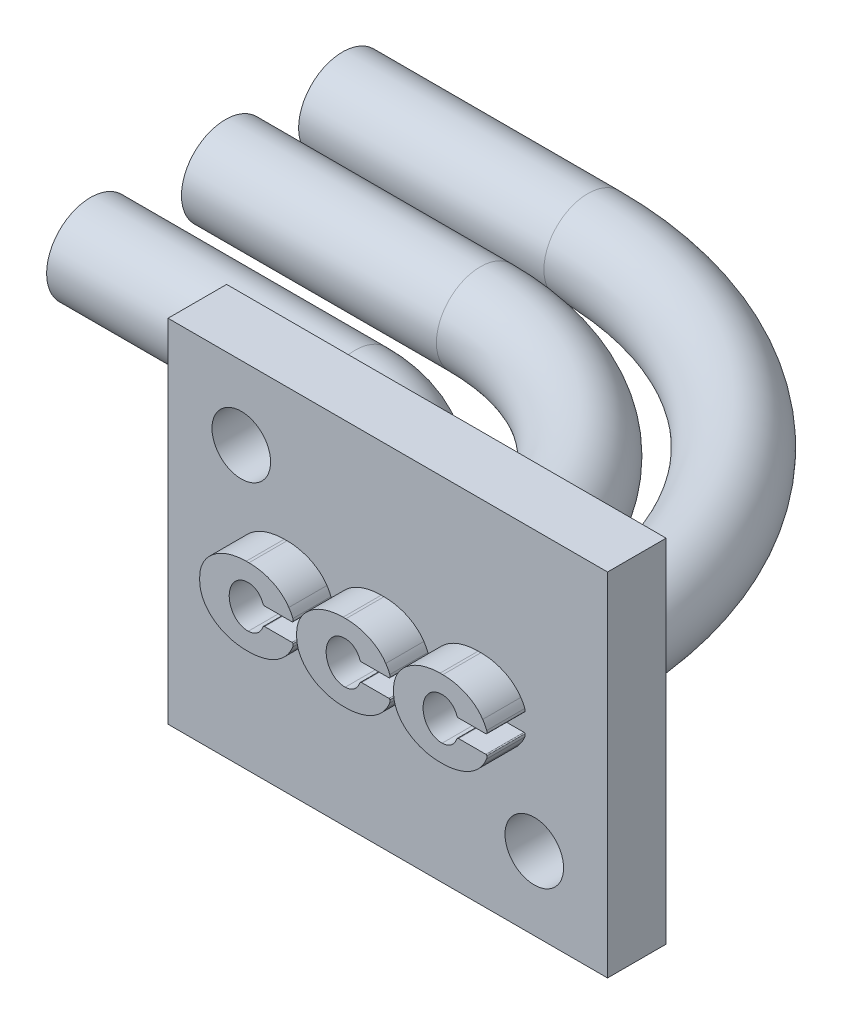
SolidWorks part; units mm, degrees
ref_plane "Front Plane" through (0, 0, 0) normal (0, 0, 1) x (1, 0, 0)
ref_plane "Top Plane" through (0, 0, 0) normal (0, 1, 0) x (1, 0, 0)
ref_plane "Right Plane" through (0, 0, 0) normal (1, 0, 0) x (0, 0, -1)
sketch "Sketch1" plane through (0, 0, 0) normal (0, 0, 1) x (1, 0, 0)
  line L1 (-7.5, 6) -> (7.5, 6)
  line L2 (-7.5, 6) -> (-7.5, -6)
  line L3 (-7.5, -6) -> (7.5, -6)
  line L4 (7.5, 6) -> (7.5, -6)
  line L5 (-7.5, 6) -> (7.5, -6) construction
  line L6 (-7.5, -6) -> (7.5, 6) construction
  point P0 (0, 0)
  dimension "D1" = 15
  dimension "D2" = 12
extrude "Boss-Extrude1" add sketch "Sketch1" along normal blind 2
sketch "Sketch2" plane through (0, 0, 2) normal (0, 0, 1) x (1, 0, 0)
  line L0 (0.4072, 0.4423) -> (1.3431, 0.4423)
  line L1 (-0.1301, 1.4531) -> (-0.2238, 1.4531)
  line L2 (-1.8094, 0.2019) -> (-1.8094, 0.0718)
  line L3 (-0.2238, -1.1794) -> (-0.1301, -1.1794)
  line L4 (1.3385, -0.1647) -> (0.4072, -0.1647)
  line L5 (-2.9011, 0.4423) -> (-1.9652, 0.4423)
  line L6 (-3.4384, 1.4531) -> (-3.5321, 1.4531)
  line L7 (-5.1177, 0.2019) -> (-5.1177, 0.0718)
  line L8 (-3.5321, -1.1794) -> (-3.4384, -1.1794)
  line L9 (-1.9698, -0.1647) -> (-2.9011, -0.1647)
  line L10 (3.7155, 0.4423) -> (4.6514, 0.4423)
  line L11 (3.1782, 1.4531) -> (3.0846, 1.4531)
  line L12 (1.4989, 0.2019) -> (1.4989, 0.0718)
  line L13 (3.0846, -1.1794) -> (3.1782, -1.1794)
  line L14 (4.6469, -0.1647) -> (3.7155, -0.1647)
  arc A0 (0.3456, 0.4859) -> (0.4072, 0.4423) centre (0.4072, 0.5078) ccw
  arc A1 (1.3431, 0.4423) -> (1.3723, 0.4672) centre (1.3386, 0.4772) ccw
  arc A2 (1.3723, 0.4672) -> (1.3681, 0.5547) centre (1.1917, 0.5024) ccw
  arc A3 (1.3681, 0.5547) -> (1.231, 0.812) centre (0.2861, 0.1431) ccw
  arc A4 (1.231, -0.5382) -> (1.3634, -0.2919) centre (0.2955, 0.1234) ccw
  arc A5 (1.3634, -0.2919) -> (1.3732, -0.1939) centre (1.1919, -0.2252) ccw
  arc A6 (1.3732, -0.1939) -> (1.3385, -0.1647) centre (1.3385, -0.1999) ccw
  arc A7 (0.4072, -0.1647) -> (0.3456, -0.2083) centre (0.4072, -0.2302) ccw
  arc A8 (-2.9627, 0.4859) -> (-2.9011, 0.4423) centre (-2.9011, 0.5078) ccw
  arc A9 (-1.9652, 0.4423) -> (-1.936, 0.4672) centre (-1.9697, 0.4772) ccw
  arc A10 (-1.936, 0.4672) -> (-1.9402, 0.5547) centre (-2.1166, 0.5024) ccw
  arc A11 (-1.9402, 0.5547) -> (-2.0773, 0.812) centre (-3.0222, 0.1431) ccw
  arc A12 (-2.0773, -0.5382) -> (-1.9449, -0.2919) centre (-3.0128, 0.1234) ccw
  arc A13 (-1.9449, -0.2919) -> (-1.9351, -0.1939) centre (-2.1164, -0.2252) ccw
  arc A14 (-1.9351, -0.1939) -> (-1.9698, -0.1647) centre (-1.9698, -0.1999) ccw
  arc A15 (-2.9011, -0.1647) -> (-2.9627, -0.2083) centre (-2.9011, -0.2302) ccw
  arc A16 (3.6539, 0.4859) -> (3.7155, 0.4423) centre (3.7155, 0.5078) ccw
  arc A17 (4.6514, 0.4423) -> (4.6806, 0.4672) centre (4.6469, 0.4772) ccw
  arc A18 (4.6806, 0.4672) -> (4.6764, 0.5547) centre (4.5, 0.5024) ccw
  arc A19 (4.6764, 0.5547) -> (4.5393, 0.812) centre (3.5944, 0.1431) ccw
  arc A20 (4.5393, -0.5382) -> (4.6717, -0.2919) centre (3.6038, 0.1234) ccw
  arc A21 (4.6717, -0.2919) -> (4.6815, -0.1939) centre (4.5002, -0.2252) ccw
  arc A22 (4.6815, -0.1939) -> (4.6469, -0.1647) centre (4.6469, -0.1999) ccw
  arc A23 (3.7155, -0.1647) -> (3.6539, -0.2083) centre (3.7155, -0.2302) ccw
  ellipse E0 centre (-0.1827, 0.137) end of major axis (-0.1791, -0.5801) minor radius 0.6209 (-0.2107, 0.8534) -> (-0.1509, -0.5792) ccw
  ellipse E1 centre (-0.2388, 0.137) end of major axis (0.0439, 0.8186) minor radius 0.6039 (0.3456, 0.4859) -> (-0.2107, 0.8534) ccw
  ellipse E2 centre (-0.2522, 0.1514) end of major axis (1.3906, 0.3966) minor radius 1.2925 (1.231, 0.812) -> (-0.1301, 1.4531) ccw
  ellipse E3 centre (-0.1614, 0.1527) end of major axis (-1.8063, 0.2821) minor radius 1.2979 (-0.2238, 1.4531) -> (-1.8094, 0.2019) ccw
  ellipse E4 centre (-0.1614, 0.121) end of major axis (1.4835, 0.2504) minor radius 1.2979 (-1.8094, 0.0718) -> (-0.2238, -1.1794) ccw
  ellipse E5 centre (-0.2522, 0.1223) end of major axis (-1.895, 0.3674) minor radius 1.2925 (-0.1301, -1.1794) -> (1.231, -0.5382) ccw
  ellipse E6 centre (-0.2388, 0.1406) end of major axis (0.0439, -0.541) minor radius 0.6039 (-0.1509, -0.5792) -> (0.3456, -0.2083) ccw
  ellipse E7 centre (-3.5471, 0.137) end of major axis (-3.2644, 0.8186) minor radius 0.6039 (-2.9627, 0.4859) -> (-3.519, 0.8534) ccw
  ellipse E8 centre (-3.5605, 0.1514) end of major axis (-1.9177, 0.3966) minor radius 1.2925 (-2.0773, 0.812) -> (-3.4384, 1.4531) ccw
  ellipse E9 centre (-3.4697, 0.1527) end of major axis (-5.1146, 0.2821) minor radius 1.2979 (-3.5321, 1.4531) -> (-5.1177, 0.2019) ccw
  ellipse E10 centre (-3.4697, 0.121) end of major axis (-1.8248, 0.2504) minor radius 1.2979 (-5.1177, 0.0718) -> (-3.5321, -1.1794) ccw
  ellipse E11 centre (-3.5605, 0.1223) end of major axis (-1.9177, -0.1229) minor radius 1.2925 (-3.4384, -1.1794) -> (-2.0773, -0.5382) ccw
  ellipse E12 centre (-3.5471, 0.1406) end of major axis (-3.8297, 0.8222) minor radius 0.6039 (-3.4592, -0.5792) -> (-2.9627, -0.2083) ccw
  ellipse E13 centre (-3.491, 0.137) end of major axis (-3.4946, 0.8541) minor radius 0.6209 (-3.519, 0.8534) -> (-3.4592, -0.5792) ccw
  ellipse E14 centre (3.1256, 0.137) end of major axis (3.1292, -0.5801) minor radius 0.6209 (3.0976, 0.8534) -> (3.1574, -0.5792) ccw
  ellipse E15 centre (3.0695, 0.137) end of major axis (3.3522, 0.8186) minor radius 0.6039 (3.6539, 0.4859) -> (3.0976, 0.8534) ccw
  ellipse E16 centre (3.0561, 0.1514) end of major axis (4.6989, 0.3966) minor radius 1.2925 (4.5393, 0.812) -> (3.1782, 1.4531) ccw
  ellipse E17 centre (3.1469, 0.1527) end of major axis (1.502, 0.2821) minor radius 1.2979 (3.0846, 1.4531) -> (1.4989, 0.2019) ccw
  ellipse E18 centre (3.1469, 0.121) end of major axis (4.7918, 0.2504) minor radius 1.2979 (1.4989, 0.0718) -> (3.0846, -1.1794) ccw
  ellipse E19 centre (3.0561, 0.1223) end of major axis (1.4133, 0.3674) minor radius 1.2925 (3.1782, -1.1794) -> (4.5393, -0.5382) ccw
  ellipse E20 centre (3.0695, 0.1406) end of major axis (3.3522, -0.541) minor radius 0.6039 (3.1574, -0.5792) -> (3.6539, -0.2083) ccw
extrude "Boss-Extrude2" add sketch "Sketch2" along normal blind 2
sketch "Sketch3" plane through (0, 0, 0) normal (0, 1, 0) x (1, 0, 0)
  line L0 (7.5, 0) -> (-7.5, 0) construction
  line L1 (2.7287, 0) -> (4.2287, 0)
  line L2 (2.7287, 0) -> (2.7287, 12.6)
  line L3 (-3.864, -2) -> (-3.864, 5.3789) construction
  line L4 (4.2287, 0) -> (4.2287, 14.1)
  line L5 (-4.614, 0) -> (-3.114, 0)
  line L6 (-4.614, 0) -> (-4.614, 4)
  line L7 (-0.1926, -2) -> (-0.1926, 4.6797) construction
  line L8 (-3.114, 0) -> (-3.114, 4)
  line L9 (-3.114, 4) -> (-4.614, 4)
  line L10 (-0.9426, 0) -> (0.5574, 0)
  line L13 (-0.9426, 0) -> (-0.9426, 8.6)
  line L14 (3.4787, -2) -> (3.4787, 2.787) construction
  line L15 (0.5574, 0) -> (0.5574, 10.1)
  line L16 (0.5574, 10.1) -> (-2.6426, 10.1)
  line L17 (-2.4226, 14.1) -> (4.2287, 14.1)
  line L18 (-0.9426, 8.6) -> (-2.6426, 8.6)
  line L19 (-2.6426, 10.1) -> (-2.6426, 8.6)
  line L20 (-2.4226, 14.1) -> (-2.4226, 12.6)
  line L21 (-2.4226, 12.6) -> (2.7287, 12.6)
  dimension "D1" = 1.5
  dimension "D2" = 4
  dimension "D3" = 1.5
  dimension "D4" = 1.5
  dimension "D5" = 4.6
  dimension "D6" = 1.5
  dimension "D7" = 2.5
  dimension "D8" = 1.5
  dimension "D9" = 1.7
  dimension "D10" = 3.4787
  dimension "D11" = 0.1926
  dimension "D12" = 3.864
extrude "Boss-Extrude3" add sketch "Sketch3" along normal mid plane 4
sketch "Sketch4" [suppressed] plane through (0, 2, 0) normal (0, 1, 0) x (1, 0, 0)
  line L1 (-2.4226, 10.1) -> (-2.4226, 8.6) construction
  line L2 (-2.894, 4) -> (-11.894, 4)
  line L3 (-2.894, 4) -> (-2.894, 5.5)
  line L4 (-2.894, 5.5) -> (-11.894, 5.5)
  line L5 (-11.894, 4) -> (-11.894, 5.5)
  dimension "D1" = 9
extrude "Boss-Extrude4" [suppressed] add sketch "Sketch4" against normal up to surface (4 mm away)
sketch "Sketch5" [suppressed] plane through (-2.4226, 0, 0) normal (-1, 0, 0) x (0, 0, 1)
  line L4 (-10.1, -2) -> (-8.6, -2)
  line L5 (-8.6, -2) -> (-8.6, 2)
  line L6 (-8.6, 2) -> (-10.1, 2)
  line L7 (-10.1, 2) -> (-10.1, -2)
  line L8 (-10.1, -2) -> (-8.6, -2)
  line L9 (-8.6, -2) -> (-8.6, 2)
  line L10 (-8.6, 2) -> (-10.1, 2)
  line L11 (-10.1, 2) -> (-10.1, -2)
  line L12 (-14.1, -2) -> (-12.6, -2)
  line L13 (-12.6, -2) -> (-12.6, 2)
  line L14 (-12.6, 2) -> (-14.1, 2)
  line L15 (-14.1, 2) -> (-14.1, -2)
  line L16 (-14.1, -2) -> (-12.6, -2)
  line L17 (-12.6, -2) -> (-12.6, 2)
  line L18 (-12.6, 2) -> (-14.1, 2)
  line L19 (-14.1, 2) -> (-14.1, -2)
  dimension "D1" = 0
  dimension "D2" = 0
extrude "Boss-Extrude5" [suppressed] add sketch "Sketch5" along normal up to surface (9.4714 mm away)
sketch "Sketch6" plane through (0, 0, 0) normal (0, 0, -1) x (-1, 0, 0)
  line L0 (-4.2287, 0) -> (-2.7287, 0) construction
  line L1 (-4.2287, 2) -> (-4.2287, -2) construction
  line L2 (-2.7287, 2) -> (-2.7287, -2) construction
  line L3 (-0.5574, 0) -> (0.9426, 0) construction
  line L4 (-0.5574, 2) -> (-0.5574, -2) construction
  line L5 (0.9426, 2) -> (0.9426, -2) construction
  line L6 (3.114, 0) -> (4.614, 0) construction
  line L7 (3.114, 2) -> (3.114, -2) construction
  line L8 (4.614, 2) -> (4.614, -2) construction
  circle A0 centre (-3.4787, 0) radius 1.5
  dimension "D1" = 3
sketch "Sketch7" plane through (0, 0, 0) normal (0, 0, -1) x (-1, 0, 0)
  circle A0 centre (0, 0) radius 1.5
  dimension "D1" = 3
sketch "Sketch8" plane through (0, 0, 0) normal (0, 0, -1) x (-1, 0, 0)
  line L0 (3.114, 0) -> (4.614, 0) construction
  circle A0 centre (3.864, 0) radius 1.5
  dimension "D1" = 3
sketch "Sketch9" plane through (0, 0, 0) normal (0, 1, 0) x (1, 0, 0)
  line L0 (-3.864, 0) -> (-3.864, 0.75)
  line L1 (-3.114, 0) -> (-4.614, 0) construction
  line L2 (-7.864, 4.75) -> (-16.894, 4.75)
  arc A0 (-3.864, 0.75) -> (-7.864, 4.75) centre (-7.864, 0.75) ccw
  point P7 (-3.864, 4.75)
  dimension "D3" = 4
  dimension "D1" = 4.75
  dimension "D2" = 13.03
sketch "Sketch10" plane through (0, 0, 0) normal (0, 1, 0) x (1, 0, 0)
  line L0 (-0.1926, 0) -> (-0.1926, 1.16)
  line L1 (0.5574, 0) -> (-0.9426, 0) construction
  line L2 (-8.1926, 9.16) -> (-16.894, 9.16)
  arc A0 (-0.1926, 1.16) -> (-8.1926, 9.16) centre (-8.1926, 1.16) ccw
  point P7 (-0.1926, 9.16)
  dimension "D3" = 8
  dimension "D1" = 16.7014
  dimension "D2" = 9.16
sketch "Sketch11" plane through (0, 0, 0) normal (0, 1, 0) x (1, 0, 0)
  line L0 (3.4787, 0) -> (3.4787, 1.35)
  line L1 (4.2287, 0) -> (2.7287, 0) construction
  line L2 (-8.5213, 13.35) -> (-16.894, 13.35)
  arc A0 (3.4787, 1.35) -> (-8.5213, 13.35) centre (-8.5213, 1.35) ccw
  point P7 (3.4787, 13.35)
  dimension "D3" = 12
  dimension "D1" = 13.35
  dimension "D2" = 20.3728
sketch "Sketch12" plane through (7.5, 0, 0) normal (1, 0, 0) x (0, 0, -1)
  line L1 (0, -6) -> (14.1, -6)
  line L2 (0, -6) -> (0, 2)
  line L3 (0, 2) -> (14.1, 2)
  line L4 (14.1, -6) -> (14.1, 2)
extrude "Cut-Extrude1" cut sketch "Sketch12" against normal through all
sweep "Sweep1" add profiles "Sketch8" path "Sketch9"
sweep "Sweep2" add profiles "Sketch7" path "Sketch10"
sweep "Sweep3" add profiles "Sketch6" path "Sketch11"
sketch "Sketch13" plane through (0, 0, 0) normal (0, 0, -1) x (-1, 0, 0)
  line L0 (-7.5, 6) -> (7.5, 6) construction
  line L1 (7.5, 6) -> (7.5, -6) construction
  line L2 (7.5, -6) -> (-7.5, -6) construction
  line L3 (-7.5, -6) -> (-7.5, 6) construction
  circle A0 centre (-5, -3.5) radius 1
  circle A1 centre (5, 3.5) radius 1
  dimension "D5" = 2
  dimension "D1" = 2.5
  dimension "D2" = 2.5
  dimension "D3" = 2.5
  dimension "D4" = 2.5
extrude "Cut-Extrude2" cut sketch "Sketch13" against normal through all
sketch "Sketch15" plane through (0, 0, 4) normal (0, 0, 1) x (1, 0, 0)
  line L0 (0.4072, 0.4423) -> (1.3431, 0.4423) construction
  line L1 (-0.1301, 1.4531) -> (-0.2238, 1.4531) construction
  line L2 (-1.8094, 0.2019) -> (-1.8094, 0.0718) construction
  line L3 (-0.2238, -1.1794) -> (-0.1301, -1.1794) construction
  line L4 (1.3385, -0.1647) -> (0.4072, -0.1647) construction
  line L5 (-2.9011, 0.4423) -> (-1.9652, 0.4423)
  line L6 (-3.4384, 1.4531) -> (-3.5321, 1.4531)
  line L7 (-5.1177, 0.2019) -> (-5.1177, 0.0718)
  line L8 (-3.5321, -1.1794) -> (-3.4384, -1.1794)
  line L9 (-1.9698, -0.1647) -> (-2.9011, -0.1647)
  line L10 (-2.9011, 0.4423) -> (-1.9652, 0.4423)
  line L11 (-3.4384, 1.4531) -> (-3.5321, 1.4531)
  line L12 (-5.1177, 0.2019) -> (-5.1177, 0.0718)
  line L13 (-3.5321, -1.1794) -> (-3.4384, -1.1794)
  line L14 (-1.9698, -0.1647) -> (-2.9011, -0.1647)
  line L15 (3.7155, 0.4423) -> (4.6514, 0.4423) construction
  line L16 (3.1782, 1.4531) -> (3.0846, 1.4531) construction
  line L17 (1.4989, 0.2019) -> (1.4989, 0.0718) construction
  line L18 (3.0846, -1.1794) -> (3.1782, -1.1794) construction
  line L19 (4.6469, -0.1647) -> (3.7155, -0.1647) construction
  line L20 (0.4072, 0.4423) -> (1.3431, 0.4423)
  line L21 (-0.1301, 1.4531) -> (-0.2238, 1.4531)
  line L22 (-1.8094, 0.2019) -> (-1.8094, 0.0718)
  line L23 (-0.2238, -1.1794) -> (-0.1301, -1.1794)
  line L24 (1.3385, -0.1647) -> (0.4072, -0.1647)
  line L25 (3.7155, 0.4423) -> (4.6514, 0.4423)
  line L26 (3.1782, 1.4531) -> (3.0846, 1.4531)
  line L27 (1.4989, 0.2019) -> (1.4989, 0.0718)
  line L28 (3.0846, -1.1794) -> (3.1782, -1.1794)
  line L29 (4.6469, -0.1647) -> (3.7155, -0.1647)
  arc A0 (0.3456, 0.4859) -> (0.4072, 0.4423) centre (0.4072, 0.5078) ccw construction
  arc A1 (1.3431, 0.4423) -> (1.3723, 0.4672) centre (1.3386, 0.4772) ccw construction
  arc A2 (1.3723, 0.4672) -> (1.3681, 0.5547) centre (1.1917, 0.5024) ccw construction
  arc A3 (1.3681, 0.5547) -> (1.231, 0.812) centre (0.2861, 0.1431) ccw construction
  arc A4 (1.231, -0.5382) -> (1.3634, -0.2919) centre (0.2955, 0.1234) ccw construction
  arc A5 (1.3634, -0.2919) -> (1.3732, -0.1939) centre (1.1919, -0.2252) ccw construction
  arc A6 (1.3732, -0.1939) -> (1.3385, -0.1647) centre (1.3385, -0.1999) ccw construction
  arc A7 (0.4072, -0.1647) -> (0.3456, -0.2083) centre (0.4072, -0.2302) ccw construction
  arc A8 (-2.9627, 0.4859) -> (-2.9011, 0.4423) centre (-2.9011, 0.5078) ccw
  arc A9 (-1.9652, 0.4423) -> (-1.936, 0.4672) centre (-1.9697, 0.4772) ccw
  arc A10 (-1.936, 0.4672) -> (-1.9402, 0.5547) centre (-2.1166, 0.5024) ccw
  arc A11 (-1.9402, 0.5547) -> (-2.0773, 0.812) centre (-3.0222, 0.1431) ccw
  arc A12 (-2.0773, -0.5382) -> (-1.9449, -0.2919) centre (-3.0128, 0.1234) ccw
  arc A13 (-1.9449, -0.2919) -> (-1.9351, -0.1939) centre (-2.1164, -0.2252) ccw
  arc A14 (-1.9351, -0.1939) -> (-1.9698, -0.1647) centre (-1.9698, -0.1999) ccw
  arc A15 (-2.9011, -0.1647) -> (-2.9627, -0.2083) centre (-2.9011, -0.2302) ccw
  arc A16 (-2.9627, 0.4859) -> (-2.9011, 0.4423) centre (-2.9011, 0.5078) ccw
  arc A17 (-1.9652, 0.4423) -> (-1.936, 0.4672) centre (-1.9697, 0.4772) ccw
  arc A18 (-1.936, 0.4672) -> (-1.9402, 0.5547) centre (-2.1166, 0.5024) ccw
  arc A19 (-1.9402, 0.5547) -> (-2.0773, 0.812) centre (-3.0222, 0.1431) ccw
  arc A20 (-2.0773, -0.5382) -> (-1.9449, -0.2919) centre (-3.0128, 0.1234) ccw
  arc A21 (-1.9449, -0.2919) -> (-1.9351, -0.1939) centre (-2.1164, -0.2252) ccw
  arc A22 (-1.9351, -0.1939) -> (-1.9698, -0.1647) centre (-1.9698, -0.1999) ccw
  arc A23 (-2.9011, -0.1647) -> (-2.9627, -0.2083) centre (-2.9011, -0.2302) ccw
  arc A24 (3.6539, 0.4859) -> (3.7155, 0.4423) centre (3.7155, 0.5078) ccw construction
  arc A25 (4.6514, 0.4423) -> (4.6806, 0.4672) centre (4.6469, 0.4772) ccw construction
  arc A26 (4.6806, 0.4672) -> (4.6764, 0.5547) centre (4.5, 0.5024) ccw construction
  arc A27 (4.6764, 0.5547) -> (4.5393, 0.812) centre (3.5944, 0.1431) ccw construction
  arc A28 (4.5393, -0.5382) -> (4.6717, -0.2919) centre (3.6038, 0.1234) ccw construction
  arc A29 (4.6717, -0.2919) -> (4.6815, -0.1939) centre (4.5002, -0.2252) ccw construction
  arc A30 (4.6815, -0.1939) -> (4.6469, -0.1647) centre (4.6469, -0.1999) ccw construction
  arc A31 (3.7155, -0.1647) -> (3.6539, -0.2083) centre (3.7155, -0.2302) ccw construction
  arc A32 (0.3456, 0.4859) -> (0.4072, 0.4423) centre (0.4072, 0.5078) ccw
  arc A33 (1.3431, 0.4423) -> (1.3723, 0.4672) centre (1.3386, 0.4772) ccw
  arc A34 (1.3723, 0.4672) -> (1.3681, 0.5547) centre (1.1917, 0.5024) ccw
  arc A35 (1.3681, 0.5547) -> (1.231, 0.812) centre (0.2861, 0.1431) ccw
  arc A36 (1.231, -0.5382) -> (1.3634, -0.2919) centre (0.2955, 0.1234) ccw
  arc A37 (1.3634, -0.2919) -> (1.3732, -0.1939) centre (1.1919, -0.2252) ccw
  arc A38 (1.3732, -0.1939) -> (1.3385, -0.1647) centre (1.3385, -0.1999) ccw
  arc A39 (0.4072, -0.1647) -> (0.3456, -0.2083) centre (0.4072, -0.2302) ccw
  arc A40 (3.6539, 0.4859) -> (3.7155, 0.4423) centre (3.7155, 0.5078) ccw
  arc A41 (4.6514, 0.4423) -> (4.6806, 0.4672) centre (4.6469, 0.4772) ccw
  arc A42 (4.6806, 0.4672) -> (4.6764, 0.5547) centre (4.5, 0.5024) ccw
  arc A43 (4.6764, 0.5547) -> (4.5393, 0.812) centre (3.5944, 0.1431) ccw
  arc A44 (4.5393, -0.5382) -> (4.6717, -0.2919) centre (3.6038, 0.1234) ccw
  arc A45 (4.6717, -0.2919) -> (4.6815, -0.1939) centre (4.5002, -0.2252) ccw
  arc A46 (4.6815, -0.1939) -> (4.6469, -0.1647) centre (4.6469, -0.1999) ccw
  arc A47 (3.7155, -0.1647) -> (3.6539, -0.2083) centre (3.7155, -0.2302) ccw
  ellipse E0 centre (-0.2388, 0.137) end of major axis (-0.5214, -0.5446) minor radius 0.6039 (0.3456, 0.4859) -> (-0.2107, 0.8534) ccw construction
  ellipse E1 centre (-0.2522, 0.1514) end of major axis (1.3906, 0.3966) minor radius 1.2925 (1.231, 0.812) -> (-0.1301, 1.4531) ccw construction
  ellipse E2 centre (-0.1614, 0.1527) end of major axis (-1.8063, 0.2821) minor radius 1.2979 (-0.2238, 1.4531) -> (-1.8094, 0.2019) ccw construction
  ellipse E3 centre (-0.1614, 0.121) end of major axis (1.4835, 0.2504) minor radius 1.2979 (-1.8094, 0.0718) -> (-0.2238, -1.1794) ccw construction
  ellipse E4 centre (-0.2522, 0.1223) end of major axis (-1.895, 0.3674) minor radius 1.2925 (-0.1301, -1.1794) -> (1.231, -0.5382) ccw construction
  ellipse E5 centre (-0.2388, 0.1406) end of major axis (0.0439, -0.541) minor radius 0.6039 (-0.1509, -0.5792) -> (0.3456, -0.2083) ccw construction
  ellipse E6 centre (-0.1827, 0.137) end of major axis (-0.1791, -0.5801) minor radius 0.6209 (-0.2107, 0.8534) -> (-0.1509, -0.5792) ccw construction
  ellipse E7 centre (-3.5471, 0.137) end of major axis (-3.8297, -0.5446) minor radius 0.6039 (-2.9627, 0.4859) -> (-3.519, 0.8534) ccw
  ellipse E8 centre (-3.5605, 0.1514) end of major axis (-5.2033, -0.0937) minor radius 1.2925 (-2.0773, 0.812) -> (-3.4384, 1.4531) ccw
  ellipse E9 centre (-3.4697, 0.1527) end of major axis (-5.1146, 0.2821) minor radius 1.2979 (-3.5321, 1.4531) -> (-5.1177, 0.2019) ccw
  ellipse E10 centre (-3.4697, 0.121) end of major axis (-1.8248, 0.2504) minor radius 1.2979 (-5.1177, 0.0718) -> (-3.5321, -1.1794) ccw
  ellipse E11 centre (-3.5605, 0.1223) end of major axis (-1.9177, -0.1229) minor radius 1.2925 (-3.4384, -1.1794) -> (-2.0773, -0.5382) ccw
  ellipse E12 centre (-3.5471, 0.1406) end of major axis (-3.2644, -0.541) minor radius 0.6039 (-3.4592, -0.5792) -> (-2.9627, -0.2083) ccw
  ellipse E13 centre (-3.491, 0.137) end of major axis (-3.4874, -0.5801) minor radius 0.6209 (-3.519, 0.8534) -> (-3.4592, -0.5792) ccw
  ellipse E14 centre (-3.5471, 0.137) end of major axis (-3.8297, -0.5446) minor radius 0.6039 (-2.9627, 0.4859) -> (-3.519, 0.8534) ccw
  ellipse E15 centre (-3.5605, 0.1514) end of major axis (-5.2033, -0.0937) minor radius 1.2925 (-2.0773, 0.812) -> (-3.4384, 1.4531) ccw
  ellipse E16 centre (-3.4697, 0.1527) end of major axis (-5.1146, 0.2821) minor radius 1.2979 (-3.5321, 1.4531) -> (-5.1177, 0.2019) ccw
  ellipse E17 centre (-3.4697, 0.121) end of major axis (-1.8248, 0.2504) minor radius 1.2979 (-5.1177, 0.0718) -> (-3.5321, -1.1794) ccw
  ellipse E18 centre (-3.5605, 0.1223) end of major axis (-5.2033, 0.3674) minor radius 1.2925 (-3.4384, -1.1794) -> (-2.0773, -0.5382) ccw
  ellipse E19 centre (-3.5471, 0.1406) end of major axis (-3.2644, -0.541) minor radius 0.6039 (-3.4592, -0.5792) -> (-2.9627, -0.2083) ccw
  ellipse E20 centre (-3.491, 0.137) end of major axis (-3.4874, -0.5801) minor radius 0.6209 (-3.519, 0.8534) -> (-3.4592, -0.5792) ccw
  ellipse E21 centre (3.0695, 0.137) end of major axis (2.7869, -0.5446) minor radius 0.6039 (3.6539, 0.4859) -> (3.0976, 0.8534) ccw construction
  ellipse E22 centre (3.0561, 0.1514) end of major axis (1.4133, -0.0937) minor radius 1.2925 (4.5393, 0.812) -> (3.1782, 1.4531) ccw construction
  ellipse E23 centre (3.1469, 0.1527) end of major axis (4.7918, 0.0234) minor radius 1.2979 (3.0846, 1.4531) -> (1.4989, 0.2019) ccw construction
  ellipse E24 centre (3.1469, 0.121) end of major axis (4.7918, 0.2504) minor radius 1.2979 (1.4989, 0.0718) -> (3.0846, -1.1794) ccw construction
  ellipse E25 centre (3.0561, 0.1223) end of major axis (1.4133, 0.3674) minor radius 1.2925 (3.1782, -1.1794) -> (4.5393, -0.5382) ccw construction
  ellipse E26 centre (3.0695, 0.1406) end of major axis (3.3522, -0.541) minor radius 0.6039 (3.1574, -0.5792) -> (3.6539, -0.2083) ccw construction
  ellipse E27 centre (3.1256, 0.137) end of major axis (3.1292, -0.5801) minor radius 0.6209 (3.0976, 0.8534) -> (3.1574, -0.5792) ccw construction
  ellipse E28 centre (-0.2388, 0.137) end of major axis (-0.5214, -0.5446) minor radius 0.6039 (0.3456, 0.4859) -> (-0.2107, 0.8534) ccw
  ellipse E29 centre (-0.2522, 0.1514) end of major axis (1.3906, 0.3966) minor radius 1.2925 (1.231, 0.812) -> (-0.1301, 1.4531) ccw
  ellipse E30 centre (-0.1614, 0.1527) end of major axis (-1.8063, 0.2821) minor radius 1.2979 (-0.2238, 1.4531) -> (-1.8094, 0.2019) ccw
  ellipse E31 centre (-0.1614, 0.121) end of major axis (1.4835, 0.2504) minor radius 1.2979 (-1.8094, 0.0718) -> (-0.2238, -1.1794) ccw
  ellipse E32 centre (-0.2522, 0.1223) end of major axis (-1.895, 0.3674) minor radius 1.2925 (-0.1301, -1.1794) -> (1.231, -0.5382) ccw
  ellipse E33 centre (-0.2388, 0.1406) end of major axis (0.0439, -0.541) minor radius 0.6039 (-0.1509, -0.5792) -> (0.3456, -0.2083) ccw
  ellipse E34 centre (-0.1827, 0.137) end of major axis (-0.1791, -0.5801) minor radius 0.6209 (-0.2107, 0.8534) -> (-0.1509, -0.5792) ccw
  ellipse E35 centre (3.0695, 0.137) end of major axis (2.7869, -0.5446) minor radius 0.6039 (3.6539, 0.4859) -> (3.0976, 0.8534) ccw
  ellipse E36 centre (3.0561, 0.1514) end of major axis (4.6989, 0.3966) minor radius 1.2925 (4.5393, 0.812) -> (3.1782, 1.4531) ccw
  ellipse E37 centre (3.1469, 0.1527) end of major axis (4.7918, 0.0234) minor radius 1.2979 (3.0846, 1.4531) -> (1.4989, 0.2019) ccw
  ellipse E38 centre (3.1469, 0.121) end of major axis (4.7918, 0.2504) minor radius 1.2979 (1.4989, 0.0718) -> (3.0846, -1.1794) ccw
  ellipse E39 centre (3.0561, 0.1223) end of major axis (1.4133, 0.3674) minor radius 1.2925 (3.1782, -1.1794) -> (4.5393, -0.5382) ccw
  ellipse E40 centre (3.0695, 0.1406) end of major axis (3.3522, -0.541) minor radius 0.6039 (3.1574, -0.5792) -> (3.6539, -0.2083) ccw
  ellipse E41 centre (3.1256, 0.137) end of major axis (3.1292, -0.5801) minor radius 0.6209 (3.0976, 0.8534) -> (3.1574, -0.5792) ccw
  dimension "D1" = 0
extrude "Cut-Extrude3" cut sketch "Sketch15" against normal blind 0.7
